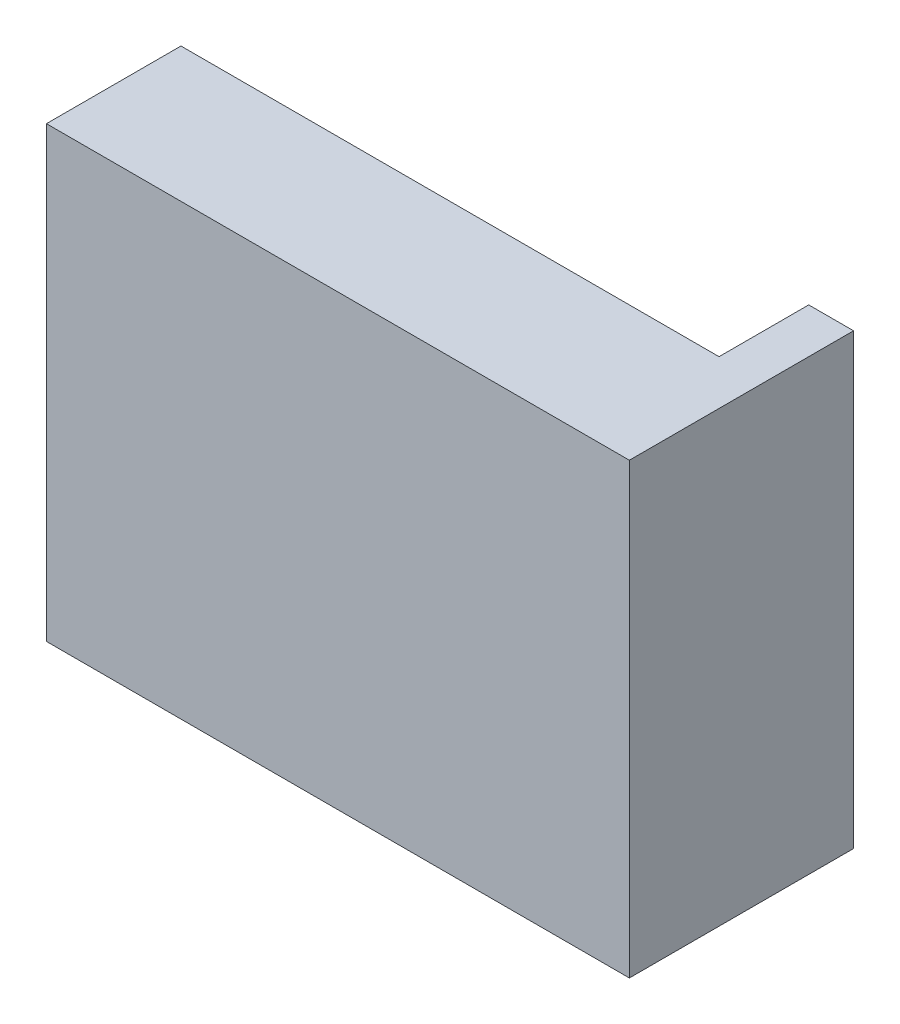
SolidWorks part; units mm, degrees
ref_plane "Plano frontal" through (0, 0, 0) normal (0, 0, 1) x (1, 0, 0)
ref_plane "Plano superior" through (0, 0, 0) normal (0, 1, 0) x (1, 0, 0)
ref_plane "Plano direito" through (0, 0, 0) normal (1, 0, 0) x (0, 0, -1)
sketch "Esboço1" plane through (0, 0, 0) normal (0, 0, 1) x (1, 0, 0)
  line L1 (0, 0) -> (-26, 0)
  line L2 (0, 0) -> (0, 20)
  line L3 (0, 20) -> (-26, 20)
  line L4 (-26, 0) -> (-26, 20)
  dimension "D1" = 26
  dimension "D2" = 20
extrude "Ressalto-extrusão1" add sketch "Esboço1" along normal blind 6
sketch "Esboço2" plane through (0, 0, 0) normal (0, 0, -1) x (-1, 0, 0)
  line L0 (0, 20) -> (26, 20) construction
  line L1 (0, 0) -> (2, 0)
  line L2 (0, 0) -> (0, 20)
  line L3 (0, 20) -> (2, 20)
  line L4 (2, 0) -> (2, 20)
  dimension "D1" = 2
extrude "Ressalto-extrusão2" add sketch "Esboço2" along normal blind 4
sketch "Esboço3" plane through (0, 0, 0) normal (0, 0, -1) x (-1, 0, 0)
  line L0 (2, 0) -> (2, 12) construction
  line L1 (2, 0) -> (2, 20) construction
  line L2 (2, 12) -> (5, 12) construction
  line L3 (5, 10) -> (26, 10)
  line L4 (5, 14) -> (26, 14)
  line L6 (26, 20) -> (26, 0) construction
  line L7 (26, 0) -> (2, 0) construction
  line L8 (26, 14) -> (26, 10)
  arc A0 (5, 14) -> (5, 10) centre (5, 12) ccw
  dimension "D3" = 4
  dimension "D1" = 12
  dimension "D2" = 3
extrude "Corte-extrusão1" cut sketch "Esboço3" against normal blind 2
